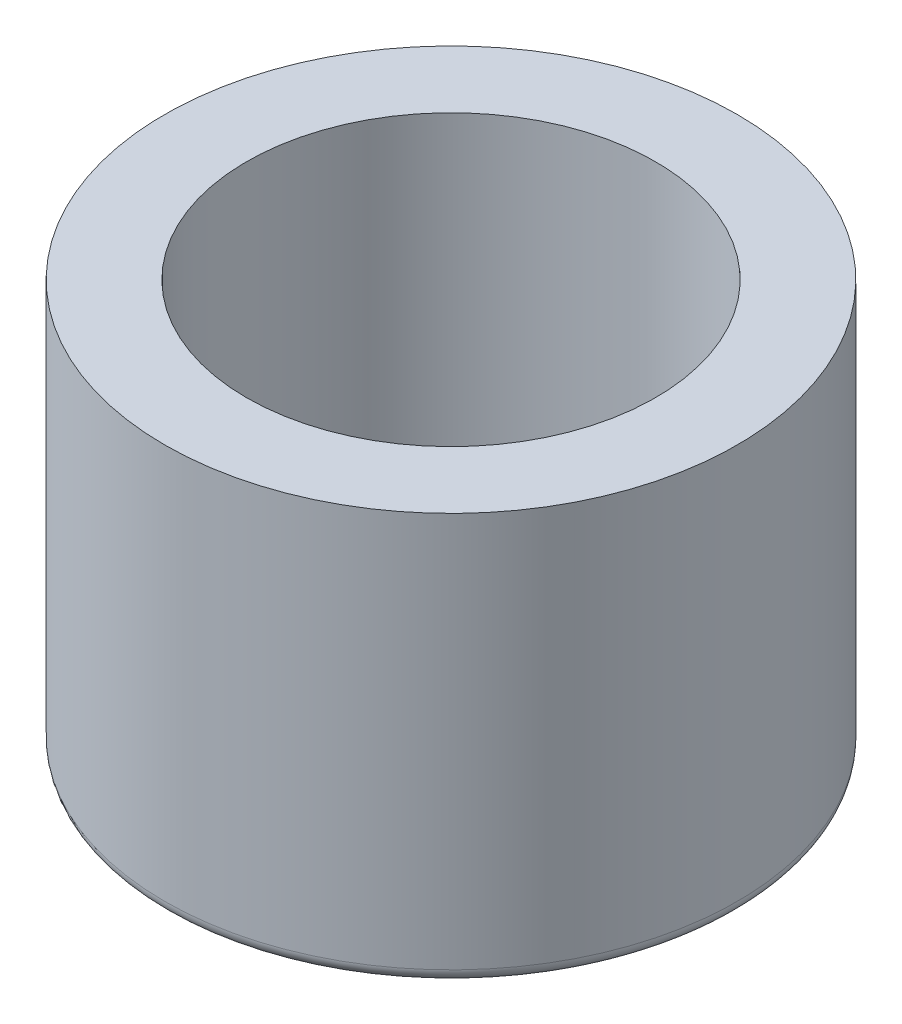
SolidWorks part; units mm, degrees
ref_plane "Front Plane" through (0, 0, 0) normal (0, 0, 1) x (1, 0, 0)
ref_plane "Top Plane" through (0, 0, 0) normal (0, 1, 0) x (1, 0, 0)
ref_plane "Right Plane" through (0, 0, 0) normal (1, 0, 0) x (0, 0, -1)
sketch "Sketch1" plane through (0, 0, 0) normal (0, 1, 0) x (1, 0, 0)
  circle A0 centre (0, 0) radius 10.5
  dimension "D1" = 21
extrude "Boss-Extrude1" add sketch "Sketch1" along normal blind 15
sketch "Sketch2" plane through (0, 15, 0) normal (0, 1, 0) x (1, 0, 0)
  circle A0 centre (0, 0) radius 7.5
  dimension "D1" = 15
extrude "Cut-Extrude1" cut sketch "Sketch2" against normal up to surface (15 mm away) up to face at (0, 0, 10.5)
fillet "Fillet1" radius 0.5 1 edges at (0, 0, 10.5)
